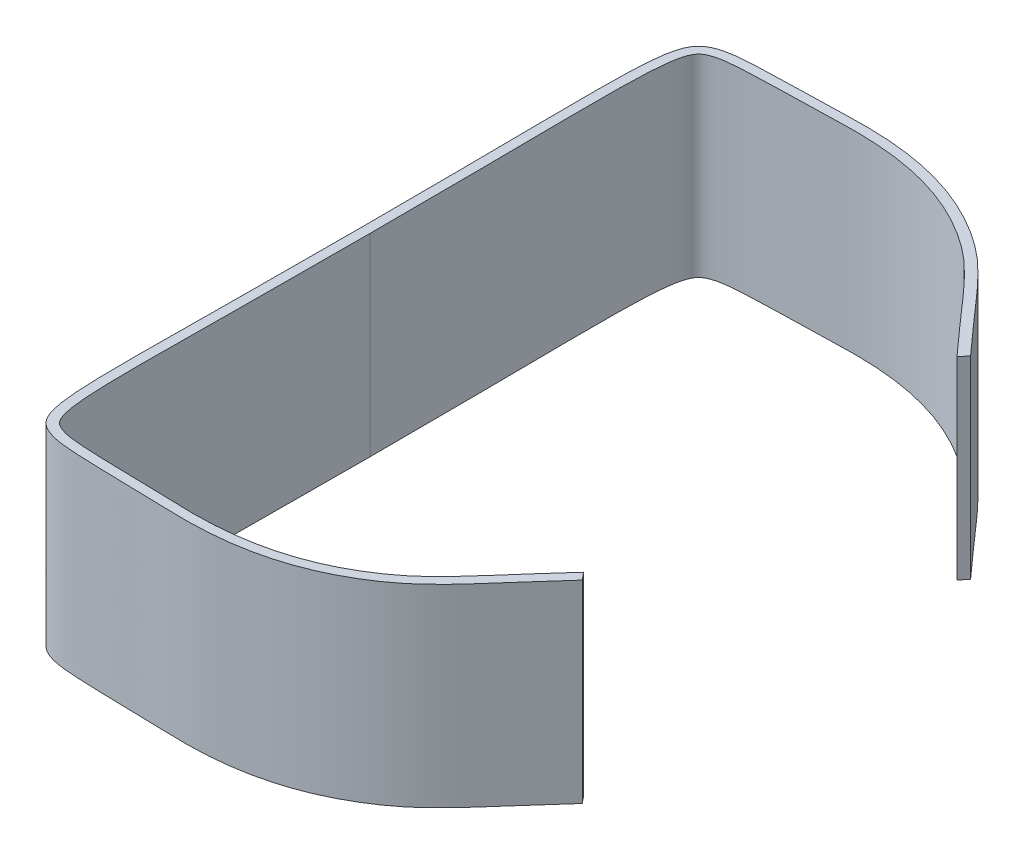
SolidWorks part; units mm, degrees
material "PLA"
ref_plane "Front Plane" through (0, 0, 0) normal (0, 0, 1) x (1, 0, 0)
ref_plane "Top Plane" through (0, 0, 0) normal (0, 1, 0) x (1, 0, 0)
ref_plane "Right Plane" through (0, 0, 0) normal (1, 0, 0) x (0, 0, -1)
sketch "Sketch1" plane through (0, 0, 0) normal (0, 1, 0) x (1, 0, 0)
  arc A0 (31.3497, -38.0693) -> (31.3497, -12.0693) centre (31.3497, -25.0693) ccw
  arc A1 (31.3497, -40.0693) -> (31.3497, -10.0693) centre (31.3497, -25.0693) ccw
  arc A2 (31.3497, -40.0693) -> (31.3497, -10.0693) centre (31.3497, -25.0693) ccw
  spline S0 degree 1 poles (31.3497, -12.0693) (-102.5003, -25.0693) knots 0 0 1 1 construction
  spline S1 degree 1 poles (-102.5003, -25.0693) (31.3497, -38.0693) knots 0 0 1 1 construction
  spline S2 degree 3 poles (-400.1867, 2959.4431) (-21.4012, -21.4544) (-130.2028, -87.9365) (-95.1723, -95.9434) (-79.4693, -96.0745) (-63.666, -96.7855) (-48.6034, -94.7613) (-29.9398, -81.014) (-19.6588, -67.0508) (54.3895, 2.5485) (-156.7681, -142.3186) (3017.9127, 231.9123) knots -0.897514 -0.897514 -0.897514 -0.897514 0.317928 0.363507 0.445537 0.481033 0.682965 0.721704 0.829683 0.858862 1.493222 1.493222 1.493222 1.493222 only from (-104.5003, -25.0693) to (31.3497, -40.0693)
  spline S3 degree 3 poles (3018.125, -282.0759) (-156.7771, 92.1863) (54.3908, -52.6883) (-19.6588, 16.9123) (-29.9398, 30.8755) (-48.6034, 44.6228) (-63.666, 46.647) (-79.4693, 45.936) (-95.1723, 45.8048) (-130.2026, 37.798) (-21.4021, -28.6836) (-400.1816, -3009.5417) knots -0.493237 -0.493237 -0.493237 -0.493237 0.141138 0.170317 0.278296 0.317035 0.518967 0.554463 0.636493 0.682072 1.897508 1.897508 1.897508 1.897508 only from (31.3497, -10.0693) to (-104.5003, -25.0693)
  spline S4 degree 3 poles (-104.5003, -25.0693) (-104.5003, -86.2204) (-106.7931, -93.2872) (-95.1723, -95.9434) (-79.4693, -96.0745) (-63.666, -96.7855) (-48.6034, -94.7613) (-29.9398, -81.014) (-19.6588, -67.0508) (7.0513, -41.9455) (5.2901, -40.0693) (31.3497, -40.0693) knots 0 0 0 0 0.317928 0.363507 0.445537 0.481033 0.682965 0.721704 0.829683 0.858862 1 1 1 1
  spline S5 degree 3 poles (31.3497, -10.0693) (5.2901, -10.0693) (7.0513, -8.1931) (-19.6588, 16.9123) (-29.9398, 30.8755) (-48.6034, 44.6228) (-63.666, 46.647) (-79.4693, 45.936) (-95.1723, 45.8048) (-106.7931, 43.1487) (-104.5003, 36.0818) (-104.5003, -25.0693) knots 0 0 0 0 0.141138 0.170317 0.278296 0.317035 0.518967 0.554463 0.636493 0.682072 1 1 1 1
  spline S6 degree 3 poles (31.3497, -12.0693) (30.6468, -12.0693) (29.2115, -12.0669) (27.235, -12.0551) (25.3574, -12.0342) (23.0041, -11.9927) (20.3185, -11.9127) (17.4651, -11.7629) (14.9349, -11.5501) (11.9328, -11.1676) (8.7634, -10.4751) (5.5939, -9.1883) (2.8815, -7.4107) (0.3957, -5.2059) (-2.2321, -2.5476) (-5.3567, 0.6457) (-9.4125, 4.5375) (-13.7609, 8.7579) (-17.6868, 12.8509) (-21.2594, 16.7718) (-25.6093, 21.7088) (-30.4043, 27.2348) (-35.451, 32.4023) (-40.235, 35.9702) (-45.0957, 38.7908) (-49.9382, 40.9204) (-54.7711, 42.4536) (-59.5761, 43.47) (-63.5451, 43.9533) (-66.6901, 44.1607) (-69.0303, 44.2365) (-71.3534, 44.2428) (-73.6409, 44.1878) (-76.1322, 44.0974) (-79.1488, 44.0116) (-82.6311, 43.9404) (-86.2768, 43.8639) (-89.829, 43.7689) (-93.0248, 43.6408) (-95.5383, 43.4676) (-97.2067, 43.2452) (-98.295, 42.998) (-99.1661, 42.7038) (-99.8642, 42.3895) (-100.3677, 42.0598) (-100.7648, 41.6822) (-101.2544, 40.9991) (-101.8532, 39.5166) (-102.3837, 36.3278) (-102.6794, 31.5686) (-102.7834, 25.0125) (-102.7581, 17.8377) (-102.7019, 10.9332) (-102.6496, 5.1373) (-102.5949, -1.3117) (-102.5539, -7.2599) (-102.5279, -12.3813) (-102.5126, -16.4069) (-102.5044, -19.9238) (-102.5009, -22.8265) (-102.5003, -24.3257) (-102.5003, -25.0693) knots 0 0 0 0 0.003906 0.007812 0.011719 0.015625 0.023438 0.03125 0.039062 0.046875 0.0625 0.078125 0.09375 0.109375 0.125 0.140625 0.15625 0.171875 0.1875 0.203125 0.21875 0.25 0.28125 0.3125 0.34375 0.375 0.40625 0.4375 0.46875 0.484375 0.5 0.515625 0.53125 0.546875 0.5625 0.578125 0.59375 0.609375 0.625 0.640625 0.65625 0.671875 0.6875 0.703125 0.71875 0.734375 0.75 0.78125 0.8125 0.84375 0.875 0.90625 0.921875 0.9375 0.953125 0.96875 0.976562 0.984375 0.992188 0.996094 1 1 1 1
  spline S7 degree 3 poles (-102.5003, -25.0693) (-102.5003, -25.8129) (-102.5009, -27.312) (-102.5044, -30.2147) (-102.5126, -33.7316) (-102.5279, -37.7573) (-102.5539, -42.8787) (-102.5949, -48.8268) (-102.6496, -55.2759) (-102.7019, -61.0718) (-102.7581, -67.9762) (-102.7834, -75.151) (-102.6794, -81.7071) (-102.3837, -86.4663) (-101.8532, -89.6552) (-101.2544, -91.1377) (-100.7648, -91.8208) (-100.3677, -92.1983) (-99.8642, -92.528) (-99.1661, -92.8424) (-98.295, -93.1366) (-97.2067, -93.3837) (-95.5383, -93.6062) (-93.0248, -93.7794) (-89.829, -93.9074) (-86.2768, -94.0024) (-82.6311, -94.079) (-79.1488, -94.1501) (-76.1322, -94.2359) (-73.6409, -94.3263) (-71.3534, -94.3813) (-69.0303, -94.375) (-66.6901, -94.2993) (-63.5451, -94.0918) (-59.5761, -93.6086) (-54.7711, -92.5921) (-49.9382, -91.059) (-45.0957, -88.9293) (-40.235, -86.1088) (-35.451, -82.5409) (-30.4043, -77.3733) (-25.6093, -71.8473) (-21.2594, -66.9103) (-17.6868, -62.9895) (-13.7609, -58.8964) (-9.4125, -54.6761) (-5.3567, -50.7842) (-2.2321, -47.591) (0.3957, -44.9326) (2.8815, -42.7279) (5.5939, -40.9502) (8.7634, -39.6634) (11.9328, -38.9709) (14.9349, -38.5885) (17.4651, -38.3756) (20.3185, -38.2259) (23.0041, -38.1459) (25.3574, -38.1043) (27.235, -38.0834) (29.2115, -38.0717) (30.6468, -38.0693) (31.3497, -38.0693) knots 0 0 0 0 0.003906 0.007812 0.015625 0.023438 0.03125 0.046875 0.0625 0.078125 0.09375 0.125 0.15625 0.1875 0.21875 0.25 0.265625 0.28125 0.296875 0.3125 0.328125 0.34375 0.359375 0.375 0.390625 0.40625 0.421875 0.4375 0.453125 0.46875 0.484375 0.5 0.515625 0.53125 0.5625 0.59375 0.625 0.65625 0.6875 0.71875 0.75 0.78125 0.796875 0.8125 0.828125 0.84375 0.859375 0.875 0.890625 0.90625 0.921875 0.9375 0.953125 0.960938 0.96875 0.976562 0.984375 0.988281 0.992188 0.996094 1 1 1 1
  dimension "D1" = 0
  dimension "D2" = 2
extrude "Boss-Extrude1" add sketch "Sketch1" along normal up to surface (40.5 mm away) contours A0 S6 S7
sketch "Sketch2" plane through (0, 40.5, 0) normal (0, 1, 0) x (1, 0, 0)
  circle A0 centre (31.3497, -25.0693) radius 63.5 construction
  circle A1 centre (31.3497, -25.0693) radius 63.5
extrude "Cut-Extrude1" cut sketch "Sketch2" against normal through all
sketch "Sketch3" plane through (0, 0, 0) normal (0, 0, 1) x (1, 0, 0)
  line L1 (-17.4458, 0) -> (-17.4458, 40.5) construction
  line L5 (-17.4458, 0) -> (-17.4458, 40.5)
  point P0 (-17.4458, 20.25)
ref_plane "Plane1" through (0, 20.25, 0) normal (0, 1, 0) x (1, 0, 0)
sketch "Sketch4" plane through (0, 20.25, 0) normal (0, 1, 0) x (1, 0, 0)
  line L0 (-48.1003, 16.0307) -> (-48.1003, 35.0807) construction
  line L1 (-98.9003, 35.0807) -> (-98.9003, 16.0307) construction
  line L2 (-48.1003, 16.0307) -> (-48.1003, 35.0807)
  line L3 (-98.9003, 35.0807) -> (-98.9003, 16.0307)
  line L4 (-98.9003, 16.0307) -> (-48.1003, 16.0307)
  point P4 (-73.5003, 16.0307)
sketch "Sketch5" plane through (0, 0, 0) normal (0, 0, 1) x (1, 0, 0)
  circle A0 centre (-73.5003, 20.25) radius 9.9634 construction
  point P0 (-73.5003, 20.25)
